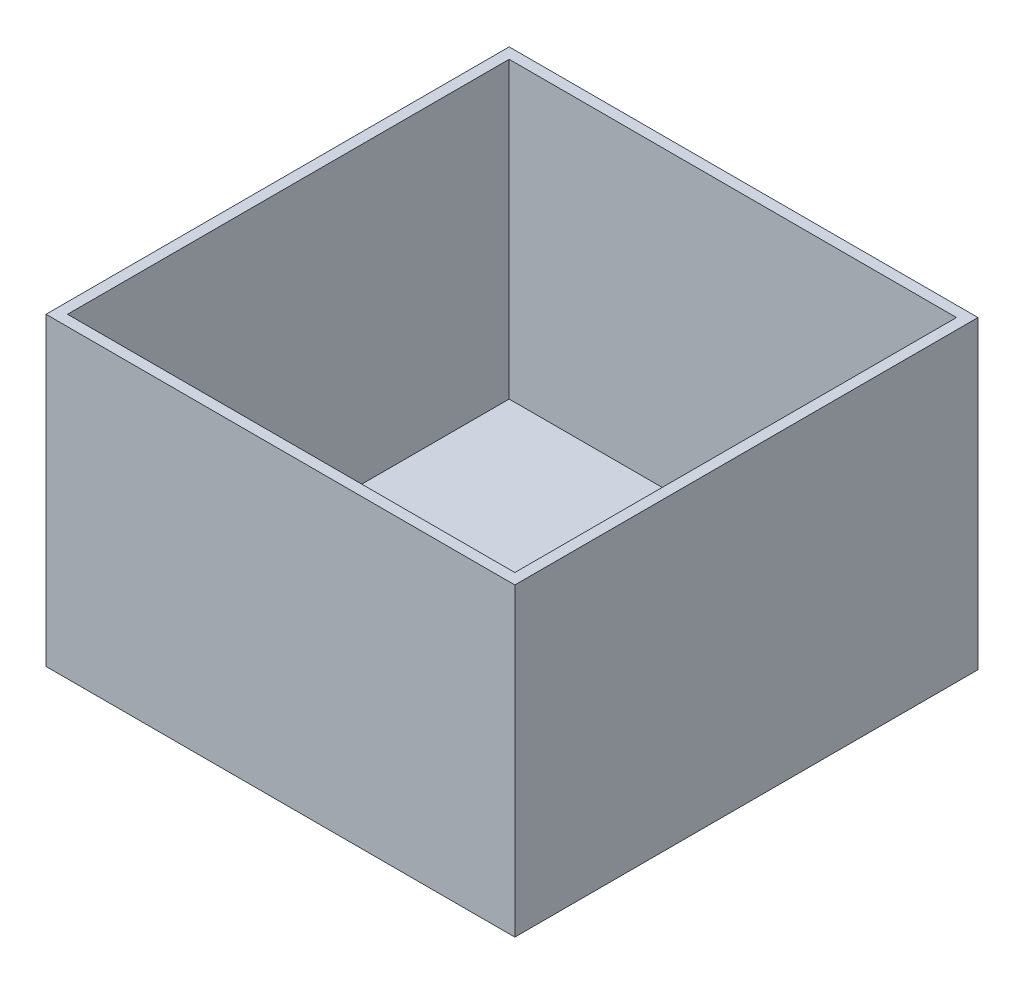
SolidWorks part; units mm, degrees
material "Acrílico (Impacto medio-alto)"
ref_plane "Front Plane" through (0, 0, 0) normal (0, 0, 1) x (1, 0, 0)
ref_plane "Top Plane" through (0, 0, 0) normal (0, 1, 0) x (1, 0, 0)
ref_plane "Right Plane" through (0, 0, 0) normal (1, 0, 0) x (0, 0, -1)
sketch "Sketch1" plane through (0, 0, 0) normal (0, 1, 0) x (1, 0, 0)
  line L1 (207.5, 205) -> (-207.5, 205)
  line L2 (207.5, 205) -> (207.5, -205)
  line L3 (207.5, -205) -> (-207.5, -205)
  line L4 (-207.5, 205) -> (-207.5, -205)
  line L5 (207.5, 205) -> (-207.5, -205) construction
  line L6 (207.5, -205) -> (-207.5, 205) construction
  point P0 (0, 0)
  dimension "D1" = 410
  dimension "D2" = 415
extrude "Boss-Extrude1" add sketch "Sketch1" along normal blind 270
sketch "Sketch2" plane through (0, 270, 0) normal (0, 1, 0) x (1, 0, 0)
  line L8 (-197.975, 195.475) -> (-197.975, -195.475)
  line L9 (-197.975, -195.475) -> (197.975, -195.475)
  line L10 (197.975, -195.475) -> (197.975, 195.475)
  line L11 (197.975, 195.475) -> (-197.975, 195.475)
  line L12 (-197.975, 195.475) -> (-197.975, -195.475)
  line L13 (-197.975, -195.475) -> (197.975, -195.475)
  line L14 (197.975, -195.475) -> (197.975, 195.475)
  line L15 (197.975, 195.475) -> (-197.975, 195.475)
  dimension "D1" = 9.525
extrude "Cut-Extrude1" cut sketch "Sketch2" against normal blind 260.475
